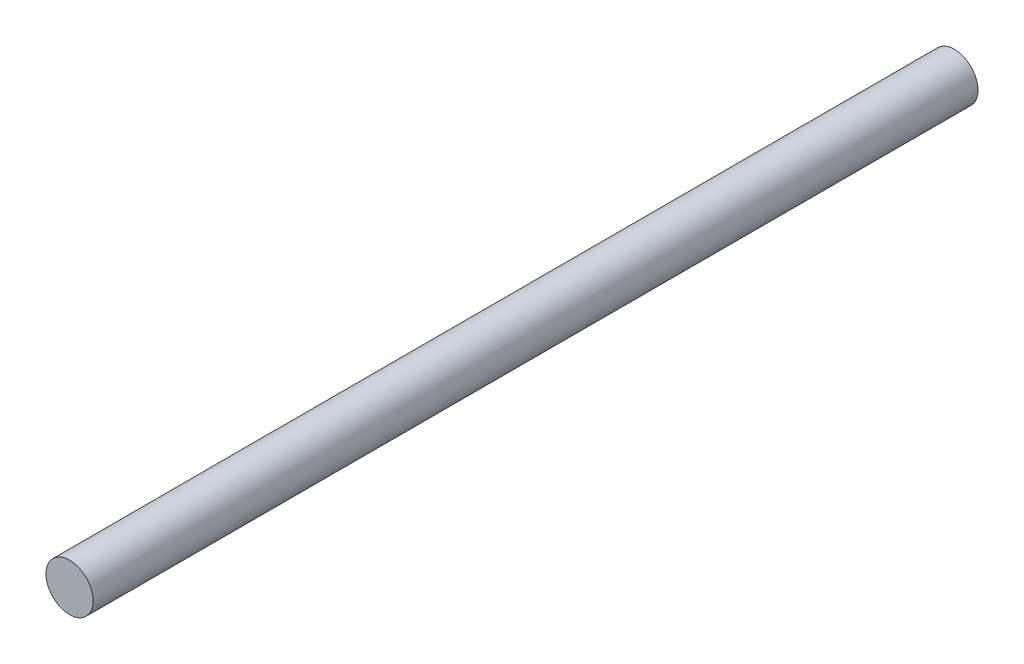
SolidWorks part; units mm, degrees
material "Хромистая нержавеющая сталь"
ref_plane "Спереди" through (0, 0, 0) normal (0, 0, 1) x (1, 0, 0)
ref_plane "Сверху" through (0, 0, 0) normal (0, 1, 0) x (1, 0, 0)
ref_plane "Справа" through (0, 0, 0) normal (1, 0, 0) x (0, 0, -1)
sketch "Эскиз1" plane through (0, 0, 0) normal (0, 0, 1) x (1, 0, 0)
  circle A0 centre (0, 0) radius 4
extrude "Бобышка-Вытянуть1" add sketch "Эскиз1" along normal blind 150
